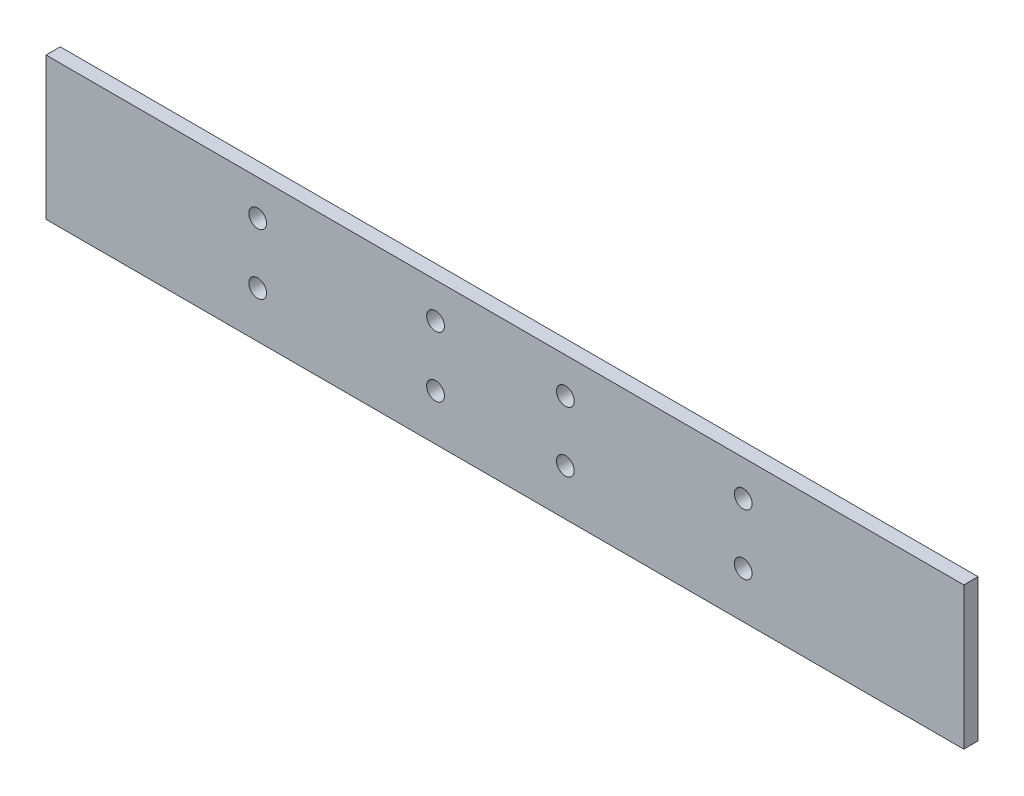
SolidWorks part; units mm, degrees
ref_plane "Front Plane" through (0, 0, 0) normal (0, 0, 1) x (1, 0, 0)
ref_plane "Top Plane" through (0, 0, 0) normal (0, 1, 0) x (1, 0, 0)
ref_plane "Right Plane" through (0, 0, 0) normal (1, 0, 0) x (0, 0, -1)
sketch "Sketch1" plane through (0, 0, 0) normal (0, 0, 1) x (1, 0, 0)
  line L1 (-129, -20) -> (129, -20)
  line L2 (-129, -20) -> (-129, 20)
  line L3 (-129, 20) -> (129, 20)
  line L4 (129, -20) -> (129, 20)
  line L5 (-129, -20) -> (129, 20) construction
  line L6 (-129, 20) -> (129, -20) construction
  circle A0 centre (-69.5, 10) radius 2.5
  circle A1 centre (-19.5, 10) radius 2.5
  circle A2 centre (17, 10) radius 2.5
  circle A3 centre (67, 10) radius 2.5
  circle A4 centre (-69.5, -7) radius 2.5
  circle A5 centre (-19.5, -7) radius 2.5
  circle A6 centre (17, -7) radius 2.5
  circle A7 centre (67, -7) radius 2.5
  point P0 (0, 0)
  dimension "D1" = 258
  dimension "D2" = 40
  dimension "D3" = 10
  dimension "D4" = 19.5
  dimension "D5" = 50
  dimension "D6" = 17
  dimension "D7" = 50
  dimension "D8" = 13
  dimension "D9" = 19.5
  dimension "D10" = 17
  dimension "D11" = 50
  dimension "D12" = 50
extrude "Boss-Extrude1" add sketch "Sketch1" along normal blind 4
